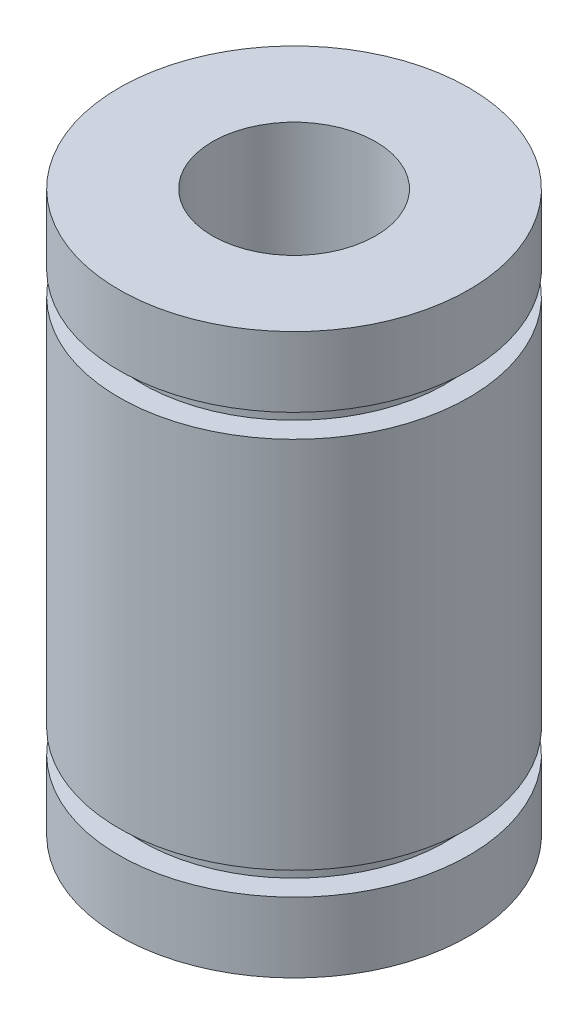
SolidWorks part; units mm, degrees
material "1060 Alloy"
ref_plane "Спереди" through (0, 0, 0) normal (0, 0, 1) x (1, 0, 0)
ref_plane "Сверху" through (0, 0, 0) normal (0, 1, 0) x (1, 0, 0)
ref_plane "Справа" through (0, 0, 0) normal (1, 0, 0) x (0, 0, -1)
sketch "Sketch1" plane through (0, 0, 0) normal (0, 0, 1) x (1, 0, 0)
  line L0 (0, 0) -> (0, 24) construction
  line L1 (0, 24) -> (-3.5, 24) construction
  line L2 (-3.5, 24) -> (-3.5, 0)
  line L3 (-3.5, 0) -> (0, 0) construction
  line L4 (-3.5, 24) -> (-7.5, 24)
  line L5 (-7.5, 24) -> (-7.5, 21)
  line L6 (-7.5, 21) -> (-6.5, 21)
  line L7 (-6.5, 21) -> (-6.5, 20)
  line L8 (-6.5, 20) -> (-7.5, 20)
  line L9 (-7.5, 20) -> (-7.5, 4)
  line L10 (-7.5, 4) -> (-6.5, 4)
  line L11 (-6.5, 4) -> (-6.5, 3)
  line L12 (-6.5, 3) -> (-7.5, 3)
  line L13 (-7.5, 3) -> (-7.5, 0)
  line L14 (-7.5, 0) -> (-3.5, 0)
  dimension "D1" = 3.5
  dimension "D2" = 24
  dimension "D3" = 1
  dimension "D4" = 3
  dimension "D5" = 7.5
  dimension "D6" = 1
  dimension "D7" = 3
revolve "Revolve1" add sketch "Sketch1" angle 360 about L0
